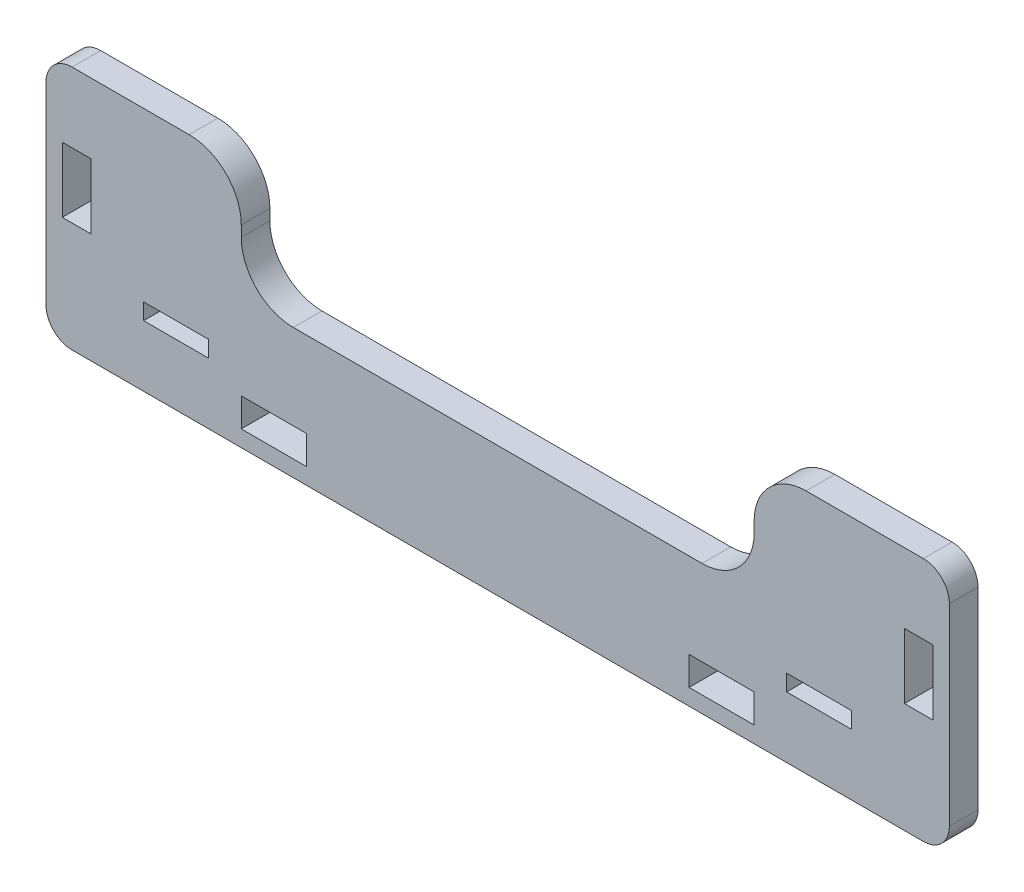
SolidWorks part; units mm, degrees
ref_plane "Front Plane" through (0, 0, 0) normal (0, 0, 1) x (1, 0, 0)
ref_plane "Top Plane" through (0, 0, 0) normal (0, 1, 0) x (1, 0, 0)
ref_plane "Right Plane" through (0, 0, 0) normal (1, 0, 0) x (0, 0, -1)
sketch "Sketch1" plane through (0, 0, 0) normal (0, 0, 1) x (1, 0, 0)
  line L0 (-69.4754, -4.3815) -> (18.6626, -4.3815)
  line L1 (18.6626, -4.3815) -> (18.6626, 19.525)
  line L2 (18.6626, 30.7975) -> (18.6626, 16.8275) construction
  line L3 (17.0751, 19.525) -> (14.2811, 19.525) construction
  line L4 (18.6626, 19.525) -> (-0.3874, 19.525)
  line L5 (-69.4754, -4.3815) -> (-69.4754, 30.7975) construction
  line L6 (-69.4754, 19.525) -> (-69.4754, -4.3815)
  line L7 (18.6626, -2.794) -> (-0.3874, -2.794) construction
  line L8 (-0.3874, 19.525) -> (-0.3874, 8.3185)
  line L10 (-0.3874, 8.3185) -> (-50.4254, 8.3185)
  line L11 (-50.4254, 8.3185) -> (-50.4254, 19.525)
  line L12 (-50.4254, -2.794) -> (-50.4254, 0) construction
  line L13 (-0.3874, -2.794) -> (-0.3874, 0) construction
  line L14 (-50.4254, 19.525) -> (-69.4754, 19.525)
  dimension "D1" = 1.5875
  dimension "D2" = 12.7
extrude "Boss-Extrude1" add sketch "Sketch1" along normal blind 2.794 contours L4 L8 L10 L11 L14 L6 L0 L1
fillet "Fillet1" radius 2.54 4 edges at (-69.4754, 19.525, 1.397) (18.6626, 19.525, 1.397) (18.6626, -4.3815, 1.397) (-69.4754, -4.3815, 1.397)
fillet "Fillet2" radius 5.08 4 edges at (-0.3874, 19.525, 1.397) (-0.3874, 8.3185, 1.397) (-50.4254, 8.3185, 1.397) (-50.4254, 19.525, 1.397)
sketch "Sketch2" plane through (0, 0, 2.794) normal (0, 0, 1) x (1, 0, 0)
  line L0 (-44.0754, 0) -> (-50.4254, 0) construction
  line L1 (-50.4254, 0) -> (-50.4254, -2.794) construction
  line L2 (-50.4254, -2.794) -> (-44.0754, -2.794) construction
  line L3 (-44.0754, -2.794) -> (-44.0754, 0) construction
  line L4 (-0.3874, 0) -> (-6.7374, 0) construction
  line L5 (-6.7374, 0) -> (-6.7374, -2.794) construction
  line L6 (-6.7374, -2.794) -> (-0.3874, -2.794) construction
  line L7 (-0.3874, -2.794) -> (-0.3874, 0) construction
  line L8 (14.2811, 12.7) -> (14.2811, 6.35) construction
  line L9 (14.2811, 6.35) -> (17.0751, 6.35) construction
  line L10 (17.0751, 6.35) -> (17.0751, 12.7) construction
  line L11 (17.0751, 12.7) -> (14.2811, 12.7) construction
  line L12 (-65.0939, 6.35) -> (-65.0939, 12.7) construction
  line L13 (-65.0939, 12.7) -> (-67.8879, 12.7) construction
  line L14 (-67.8879, 12.7) -> (-67.8879, 6.35) construction
  line L15 (-67.8879, 6.35) -> (-65.0939, 6.35) construction
  line L16 (-44.0754, 0) -> (-50.4254, 0)
  line L17 (-50.4254, 0) -> (-50.4254, -2.794)
  line L18 (-50.4254, -2.794) -> (-44.0754, -2.794)
  line L19 (-44.0754, -2.794) -> (-44.0754, 0)
  line L20 (-0.3874, 0) -> (-6.7374, 0)
  line L21 (-6.7374, 0) -> (-6.7374, -2.794)
  line L22 (-6.7374, -2.794) -> (-0.3874, -2.794)
  line L23 (-0.3874, -2.794) -> (-0.3874, 0)
  line L24 (14.2811, 12.7) -> (14.2811, 6.35)
  line L25 (14.2811, 6.35) -> (17.0751, 6.35)
  line L26 (17.0751, 6.35) -> (17.0751, 12.7)
  line L27 (17.0751, 12.7) -> (14.2811, 12.7)
  line L28 (-65.0939, 6.35) -> (-65.0939, 12.7)
  line L29 (-65.0939, 12.7) -> (-67.8879, 12.7)
  line L30 (-67.8879, 12.7) -> (-67.8879, 6.35)
  line L31 (-67.8879, 6.35) -> (-65.0939, 6.35)
  line L32 (18.6626, 0) -> (-0.3874, 0) construction
  line L33 (2.7876, 3.175) -> (9.1376, 3.175)
  line L34 (2.7876, 3.175) -> (2.7876, 1.5875)
  line L35 (2.7876, 1.5875) -> (9.1376, 1.5875)
  line L36 (9.1376, 3.175) -> (9.1376, 1.5875)
  line L38 (-53.6004, 3.175) -> (-59.9504, 3.175)
  line L39 (-53.6004, 3.175) -> (-53.6004, 1.5875)
  line L40 (-53.6004, 1.5875) -> (-59.9504, 1.5875)
  line L41 (-59.9504, 3.175) -> (-59.9504, 1.5875)
  dimension "D1" = 6.35
  dimension "D2" = 1.5875
  dimension "D3" = 1.5875
  dimension "D4" = 3.175
  dimension "D5" = 6.35
  dimension "D6" = 3.175
extrude "Cut-Extrude1" cut sketch "Sketch2" against normal through all
equation "\"D1@Boss-Extrude1\"=\"thick@assy.sldasm\""
